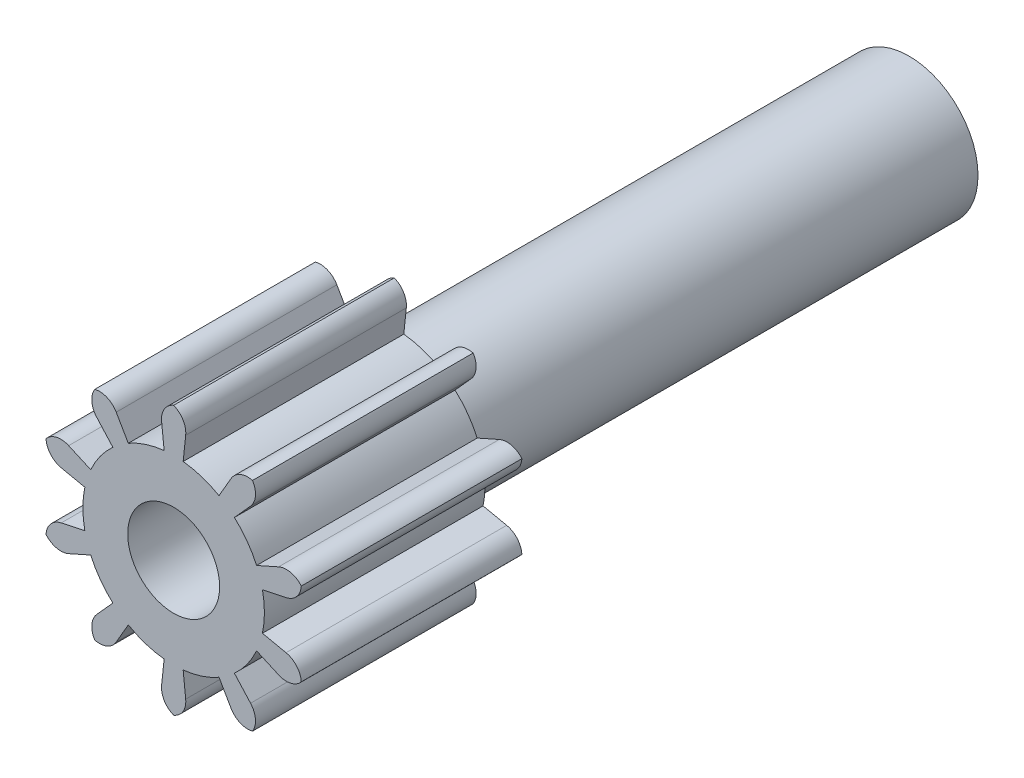
SolidWorks part; units mm, degrees
material "AISI 347 Annealed Stainless Steel (SS)"
ref_plane "Front Plane" through (0, 0, 0) normal (0, 0, 1) x (1, 0, 0)
ref_plane "Top Plane" through (0, 0, 0) normal (0, 1, 0) x (1, 0, 0)
ref_plane "Right Plane" through (0, 0, 0) normal (1, 0, 0) x (0, 0, -1)
sketch "Sketch1" plane through (0, 0, 0) normal (0, 0, 1) x (1, 0, 0)
  line L0 (0, 0) -> (0, 2.1489) construction
  line L1 (-0.1035, 0.9821) -> (-0.1311, 1.2431)
  line L2 (0.1035, 0.9821) -> (0.1311, 1.2431)
  line L3 (0.661, 0.7336) -> (0.8367, 0.9287)
  line L4 (0.4935, 0.8554) -> (0.6246, 1.0827)
  line L5 (0.966, 0.205) -> (1.2228, 0.2595)
  line L6 (0.902, 0.4019) -> (1.1418, 0.5088)
  line L7 (0.902, -0.4019) -> (1.1418, -0.5088)
  line L8 (0.966, -0.205) -> (1.2228, -0.2595)
  line L9 (0.4935, -0.8554) -> (0.6246, -1.0827)
  line L10 (0.661, -0.7336) -> (0.8367, -0.9287)
  line L11 (-0.1035, -0.9821) -> (-0.1311, -1.2431)
  line L12 (0.1035, -0.9821) -> (0.1311, -1.2431)
  line L13 (-0.661, -0.7336) -> (-0.8367, -0.9287)
  line L14 (-0.4935, -0.8554) -> (-0.6246, -1.0827)
  line L15 (-0.966, -0.205) -> (-1.2228, -0.2595)
  line L16 (-0.902, -0.4019) -> (-1.1418, -0.5088)
  line L17 (-0.902, 0.4019) -> (-1.1418, 0.5088)
  line L18 (-0.966, 0.205) -> (-1.2228, 0.2595)
  line L19 (-0.4935, 0.8554) -> (-0.6246, 1.0827)
  line L20 (-0.661, 0.7336) -> (-0.8367, 0.9287)
  arc A0 (-0.1035, 0.9821) -> (-0.4935, 0.8554) centre (0, 0) ccw
  arc A1 (-0.661, 0.7336) -> (-0.902, 0.4019) centre (0, 0) ccw
  arc A2 (0.4935, 0.8554) -> (0.1035, 0.9821) centre (0, 0) ccw
  arc A3 (-0.1311, 1.2431) -> (0, 1.46) centre (0.0775, 1.2651) cw
  arc A4 (0.1311, 1.2431) -> (0, 1.46) centre (-0.0775, 1.2651) ccw
  arc A5 (0.6246, 1.0827) -> (0.8582, 1.1812) centre (0.8063, 0.9779) cw
  arc A6 (0.8367, 0.9287) -> (0.8582, 1.1812) centre (0.6809, 1.0691) ccw
  arc A7 (1.1418, 0.5088) -> (1.3885, 0.4512) centre (1.2271, 0.3172) cw
  arc A8 (1.2228, 0.2595) -> (1.3885, 0.4512) centre (1.1792, 0.4647) ccw
  arc A9 (1.2228, -0.2595) -> (1.3885, -0.4512) centre (1.1792, -0.4647) cw
  arc A10 (1.1418, -0.5088) -> (1.3885, -0.4512) centre (1.2271, -0.3172) ccw
  arc A11 (0.8367, -0.9287) -> (0.8582, -1.1812) centre (0.6809, -1.0691) cw
  arc A12 (0.6246, -1.0827) -> (0.8582, -1.1812) centre (0.8063, -0.9779) ccw
  arc A13 (0.1311, -1.2431) -> (0, -1.46) centre (-0.0775, -1.2651) cw
  arc A14 (-0.1311, -1.2431) -> (0, -1.46) centre (0.0775, -1.2651) ccw
  arc A15 (-0.6246, -1.0827) -> (-0.8582, -1.1812) centre (-0.8063, -0.9779) cw
  arc A16 (-0.8367, -0.9287) -> (-0.8582, -1.1812) centre (-0.6809, -1.0691) ccw
  arc A17 (-1.1418, -0.5088) -> (-1.3885, -0.4512) centre (-1.2271, -0.3172) cw
  arc A18 (-1.2228, -0.2595) -> (-1.3885, -0.4512) centre (-1.1792, -0.4647) ccw
  arc A19 (-1.2228, 0.2595) -> (-1.3885, 0.4512) centre (-1.1792, 0.4647) cw
  arc A20 (-1.1418, 0.5088) -> (-1.3885, 0.4512) centre (-1.2271, 0.3172) ccw
  arc A21 (-0.8367, 0.9287) -> (-0.8582, 1.1812) centre (-0.6809, 1.0691) cw
  arc A22 (-0.6246, 1.0827) -> (-0.8582, 1.1812) centre (-0.8063, 0.9779) ccw
  arc A23 (0.902, 0.4019) -> (0.661, 0.7336) centre (0, 0) ccw
  arc A24 (0.966, -0.205) -> (0.966, 0.205) centre (0, 0) ccw
  arc A25 (0.661, -0.7336) -> (0.902, -0.4019) centre (0, 0) ccw
  arc A26 (0.1035, -0.9821) -> (0.4935, -0.8554) centre (0, 0) ccw
  arc A27 (-0.4935, -0.8554) -> (-0.1035, -0.9821) centre (0, 0) ccw
  arc A28 (-0.902, -0.4019) -> (-0.661, -0.7336) centre (0, 0) ccw
  arc A29 (-0.966, 0.205) -> (-0.966, -0.205) centre (0, 0) ccw
  circle A30 centre (0, 0) radius 0.75
  point P78 (0, 0)
  dimension "D1" = 2.92
  dimension "D2" = 1.975
  dimension "D3" = 1.5
  dimension "D4" = 10
extrude "Boss-Extrude1" add sketch "Sketch1" along normal blind 2.4
sketch "Sketch2" plane through (0, 0, 2.4) normal (0, 0, 1) x (1, 0, 0)
  circle A0 centre (0, 0) radius 0.5
  circle A1 centre (0, 0) radius 0.75
  dimension "D1" = 1.5
  dimension "D2" = 1
extrude "Boss-Extrude2" add sketch "Sketch2" against normal blind 8
